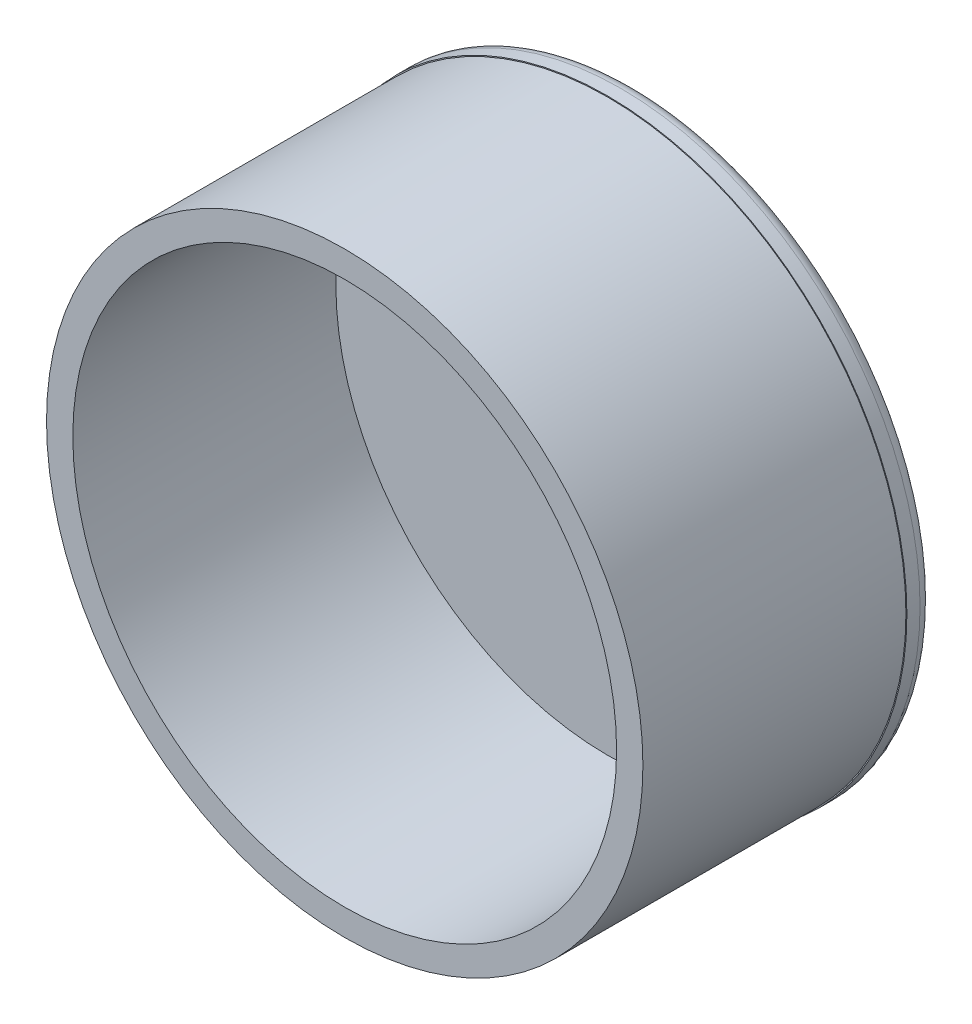
SolidWorks part; units mm, degrees
ref_plane "Front Plane" through (0, 0, 0) normal (0, 0, 1) x (1, 0, 0)
ref_plane "Top Plane" through (0, 0, 0) normal (0, 1, 0) x (1, 0, 0)
ref_plane "Right Plane" through (0, 0, 0) normal (1, 0, 0) x (0, 0, -1)
sketch "Sketch1" plane through (0, 0, 0) normal (0, 0, 1) x (1, 0, 0)
  circle A0 centre (0, 0) radius 22.75
  dimension "D1" = 45.5
extrude "Boss-Extrude1" add sketch "Sketch1" along normal blind 2
sketch "Sketch2" plane through (0, 0, 2) normal (0, 0, 1) x (1, 0, 0)
  circle A0 centre (0, 0) radius 22.6754
  circle A1 centre (0, 0) radius 20.6754
  dimension "D1" = 2
extrude "Boss-Extrude2" add sketch "Sketch2" along normal blind 20
fillet "Fillet1" radius 1 1 edges at (22.75, 0, 0)
